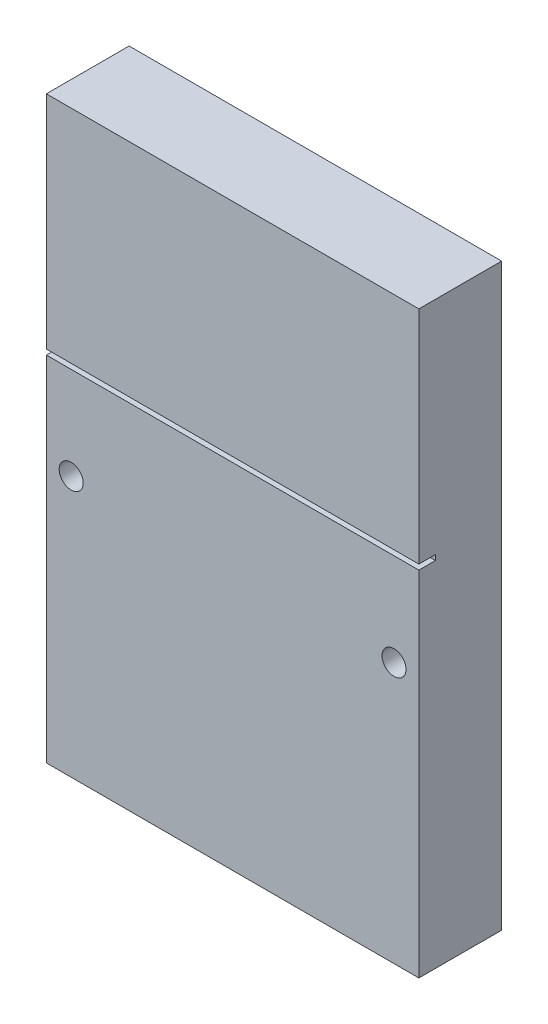
SolidWorks part; units mm, degrees
ref_plane "Front Plane" through (0, 0, 0) normal (0, 0, 1) x (1, 0, 0)
ref_plane "Top Plane" through (0, 0, 0) normal (0, 1, 0) x (1, 0, 0)
ref_plane "Right Plane" through (0, 0, 0) normal (1, 0, 0) x (0, 0, -1)
sketch "Sketch2" plane through (0, 0, 0) normal (0, 1, 0) x (1, 0, 0)
  line L1 (22.5, 5) -> (-22.5, 5)
  line L2 (22.5, 5) -> (22.5, -5)
  line L3 (22.5, -5) -> (-22.5, -5)
  line L4 (-22.5, 5) -> (-22.5, -5)
  line L5 (22.5, 5) -> (-22.5, -5) construction
  line L6 (22.5, -5) -> (-22.5, 5) construction
  point P0 (0, 0)
  dimension "D1" = 10
  dimension "D2" = 45
extrude "Boss-Extrude1" add sketch "Sketch2" along normal blind 40
sketch "Sketch3" plane through (0, 0, -5) normal (0, 0, -1) x (-1, 0, 0)
  line L0 (0, 0) -> (0, 40) construction
  line L1 (-22.5, 40) -> (22.5, 40) construction
  line L3 (22.5, 40) -> (22.5, 0) construction
  line L4 (-22.5, 40) -> (-22.5, 0) construction
  line L5 (-22.5, 0) -> (22.5, 0) construction
  line L6 (-22.5, 11.5) -> (22.5, 11.5) construction
  circle A0 centre (19.5, 2.25) radius 1.45
  circle A3 centre (-19.5, 2.25) radius 1.45
  circle A4 centre (-19.5, 20.75) radius 1.45
  circle A5 centre (19.5, 20.75) radius 1.45
  dimension "D3" = 2.9
  dimension "D4" = 3
  dimension "D1" = 3
  dimension "D2" = 2.25
sketch "Sketch4" plane through (0, 40, 0) normal (0, 1, 0) x (1, 0, 0)
  line L1 (-22.5, 5) -> (22.5, 5)
  line L2 (-22.5, 5) -> (-22.5, -5)
  line L3 (-22.5, -5) -> (22.5, -5)
  line L4 (22.5, 5) -> (22.5, -5)
extrude "Boss-Extrude2" add sketch "Sketch4" along normal blind 10
sketch "Sketch6" plane through (0, 0, -5) normal (0, 0, -1) x (-1, 0, 0)
  line L2 (-22.5, 23) -> (22.7712, 23) construction
  circle A1 centre (-19.5, 20.75) radius 1.45 construction
  dimension "D1" = 2.25
sketch "Sketch8" plane through (0, 0, 0) normal (0, -1, 0) x (1, 0, 0)
  line L1 (-22.5, 5) -> (22.5, 5)
  line L2 (-22.5, 5) -> (-22.5, -5)
  line L3 (-22.5, -5) -> (22.5, -5)
  line L4 (22.5, 5) -> (22.5, -5)
extrude "Boss-Extrude3" add sketch "Sketch8" along normal blind 20
sketch "Sketch9" plane through (0, 0, 5) normal (0, 0, 1) x (1, 0, 0)
  line L0 (22.5, 11.5) -> (-22.5, 11.5) construction
  line L1 (-22.5, 50) -> (-22.5, -20) construction
  line L2 (22.5, 50) -> (22.5, -20) construction
  circle A0 centre (19.5, 20.75) radius 1.45 construction
  circle A1 centre (19.5, 2.25) radius 1.45 construction
  circle A2 centre (19.5, 11.5) radius 1.45
  circle A3 centre (-19.5, 11.5) radius 1.45
  point P14 (0, 0)
  point P15 (0, 0)
  point P16 (0, 0)
  point P17 (0, 0)
  dimension "D1" = 18.5
  dimension "D2" = 3
  dimension "D3" = 3
  dimension "D4" = 3
extrude "Cut-Extrude2" cut sketch "Sketch9" against normal blind 20
sketch "Sketch10" plane through (0, 0, 5) normal (0, 0, 1) x (1, 0, 0)
  line L1 (-22.5, 50) -> (-22.5, -20) construction
  line L2 (-22.5, 23.2975) -> (22.5, 23.2975)
  line L3 (-22.5, 23.2975) -> (-22.5, 22.6713)
  line L4 (-22.5, 22.6713) -> (22.5, 22.6713)
  line L5 (22.5, 23.2975) -> (22.5, 22.6713)
  line L6 (22.5, 50) -> (22.5, -20) construction
extrude "Cut-Extrude3" cut sketch "Sketch10" against normal blind 2
